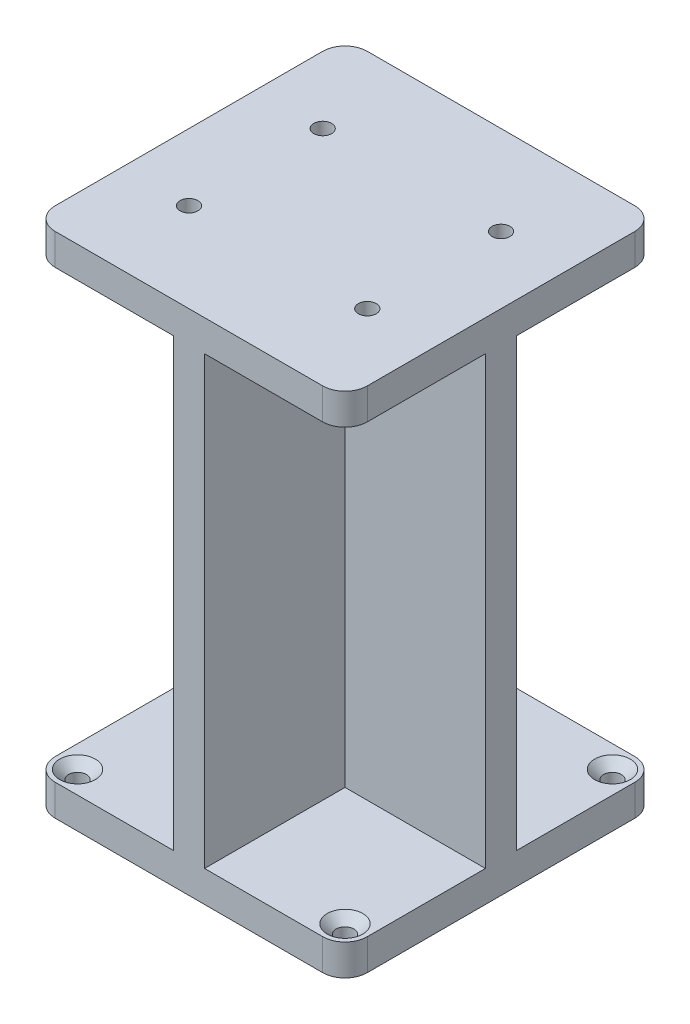
SolidWorks part; units mm, degrees
ref_plane "Front Plane" through (0, 0, 0) normal (0, 0, 1) x (1, 0, 0)
ref_plane "Top Plane" through (0, 0, 0) normal (0, 1, 0) x (1, 0, 0)
ref_plane "Right Plane" through (0, 0, 0) normal (1, 0, 0) x (0, 0, -1)
sketch "Sketch1" plane through (0, 0, 0) normal (0, 1, 0) x (1, 0, 0)
  line L0 (0, 20) -> (0, -16.1207) construction
  line L1 (-30, 35) -> (30, 35)
  line L2 (-35, 30) -> (-35, -30)
  line L3 (-30, -35) -> (30, -35)
  line L4 (35, 30) -> (35, -30)
  line L5 (-35, 35) -> (35, -35) construction
  line L6 (-35, -35) -> (35, 35) construction
  line L7 (-18.374, 0) -> (20, 0) construction
  arc A0 (30, 35) -> (35, 30) centre (30, 30) cw
  arc A1 (35, -30) -> (30, -35) centre (30, -30) cw
  arc A2 (-35, -30) -> (-30, -35) centre (-30, -30) ccw
  arc A3 (-35, 30) -> (-30, 35) centre (-30, 30) cw
  circle A4 centre (30, 30) radius 2
  circle A5 centre (-30, 30) radius 2
  circle A6 centre (30, -30) radius 2
  circle A7 centre (-30, -30) radius 2
  point P0 (0, 0)
  dimension "D2" = 5
  dimension "D3" = 4
  dimension "D1" = 70
extrude "Boss-Extrude1" add sketch "Sketch1" along normal mid plane 7
sketch "Sketch2" plane through (0, 3.5, 0) normal (0, 1, 0) x (1, 0, 0)
  line L0 (-3.5, 3.5) -> (-0.35, 3.5) construction
  line L1 (-3.5, 35) -> (3.5, 35)
  line L2 (-3.5, 35) -> (-3.5, 3.5)
  line L3 (-3.5, -35) -> (3.5, -35)
  line L4 (3.5, 35) -> (3.5, 3.5)
  line L5 (-3.5, 35) -> (3.5, -35) construction
  line L6 (-3.5, -35) -> (3.5, 35) construction
  line L7 (-35, 3.5) -> (-3.5, 3.5)
  line L8 (-35, 3.5) -> (-35, -3.5)
  line L9 (-35, -3.5) -> (-3.5, -3.5)
  line L10 (35, 3.5) -> (35, -3.5)
  line L11 (-35, 3.5) -> (35, -3.5) construction
  line L12 (-35, -3.5) -> (35, 3.5) construction
  line L13 (-0.35, 3.5) -> (0.35, 3.5) construction
  line L14 (-3.5, 3.5) -> (-3.5, 0.35) construction
  line L15 (-3.5, 0.35) -> (-3.5, -0.35) construction
  line L16 (-3.5, -0.35) -> (-3.5, -3.5) construction
  line L17 (-3.5, -3.5) -> (-3.5, -35)
  line L18 (-3.5, -3.5) -> (-0.35, -3.5) construction
  line L19 (-0.35, -3.5) -> (0.35, -3.5) construction
  line L20 (0.35, -3.5) -> (3.5, -3.5) construction
  line L21 (3.5, -3.5) -> (35, -3.5)
  line L22 (3.5, -0.35) -> (3.5, -3.5) construction
  line L23 (3.5, -3.5) -> (3.5, -35)
  line L24 (0.35, 3.5) -> (3.5, 3.5) construction
  line L25 (3.5, 3.5) -> (35, 3.5)
  line L26 (3.5, 3.5) -> (3.5, 0.35) construction
  line L27 (3.5, 0.35) -> (3.5, -0.35) construction
  line L28 (30, 35) -> (-30, 35) construction
  point P0 (0, 0)
  point P5 (0, 0)
  dimension "D1" = 7
  dimension "D2" = 7
  dimension "D3" = 70
extrude "Boss-Extrude2" add sketch "Sketch2" along normal blind 100
sketch "Sketch3" plane through (0, 103.5, 0) normal (0, 1, 0) x (1, 0, 0)
  line L0 (0, 36.6469) -> (0, -37.9185) construction
  line L1 (30, -35) -> (-30, -35)
  line L2 (35, -30) -> (35, 30)
  line L3 (30, 35) -> (-30, 35)
  line L4 (-35, -30) -> (-35, 30)
  line L5 (35, -35) -> (-35, 35) construction
  line L6 (35, 35) -> (-35, -35) construction
  line L7 (-40.659, 0) -> (48.9233, 0) construction
  line L8 (20, 30) -> (20, -24.477) construction
  arc A0 (30, 35) -> (35, 30) centre (30, 30) cw
  arc A1 (35, -30) -> (30, -35) centre (30, -30) cw
  arc A2 (-30, -35) -> (-35, -30) centre (-30, -30) cw
  arc A3 (-30, 35) -> (-35, 30) centre (-30, 30) ccw
  circle A8 centre (20, -15) radius 2
  circle A9 centre (20, 15) radius 2
  circle A10 centre (-20, 15) radius 2
  circle A11 centre (-20, -15) radius 2
  point P0 (0, 0)
  point P28 (0, 0)
  point P29 (0, 0)
  point P30 (19, -23.1176)
  point P31 (19, -22.011)
  point P32 (19, -22.011)
  point P33 (19, 21.7005)
  point P34 (19, 21.6609)
  point P35 (19, 14.2727)
  dimension "D2" = 5
  dimension "D3" = 15
  dimension "D4" = 30
  dimension "D5" = 4
  dimension "D1" = 70
extrude "Boss-Extrude3" add sketch "Sketch3" along normal blind 7
chamfer "Chamfer1" distance 2 angle 45 4 edges at (30, 3.5, 28) (-30, 3.5, 32) (30, 3.5, -28) (-30, 3.5, -32)
